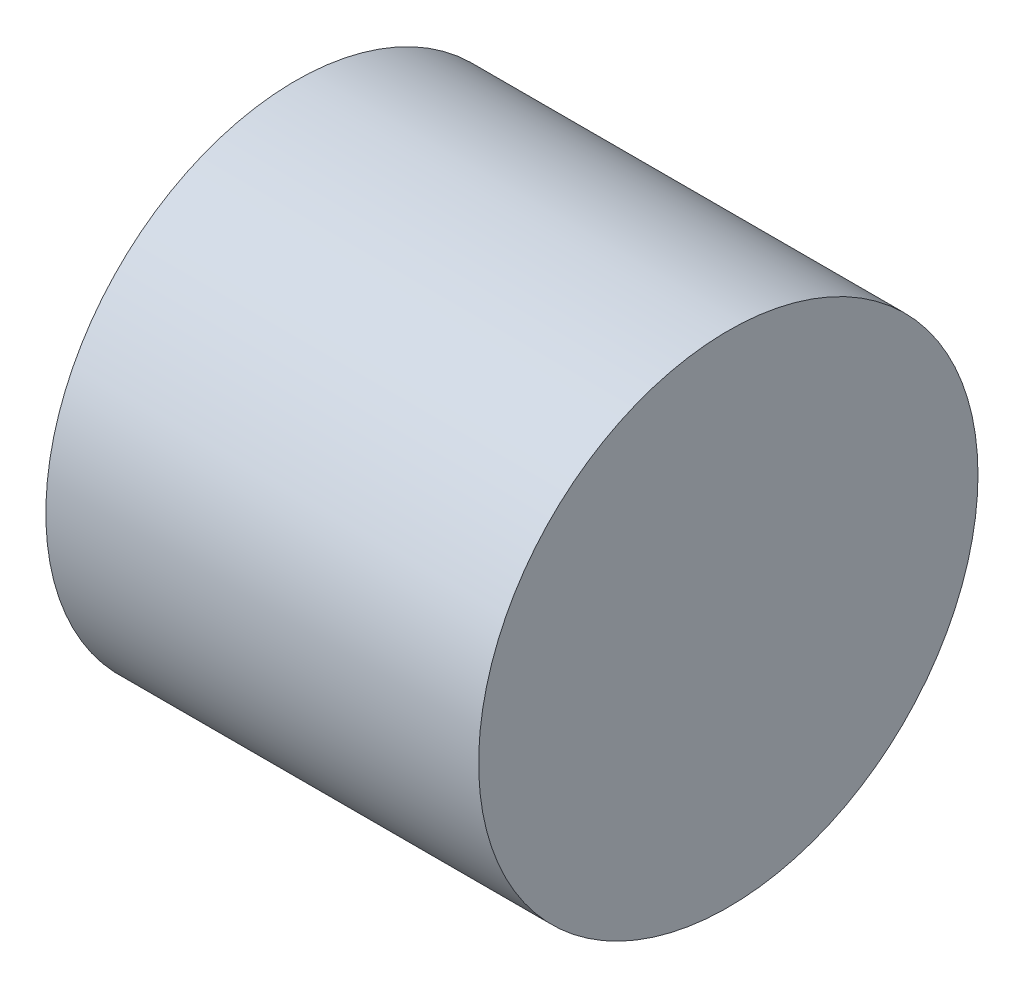
SolidWorks part; units mm, degrees
ref_plane "前视基准面" through (0, 0, 0) normal (0, 0, 1) x (1, 0, 0)
ref_plane "上视基准面" through (0, 0, 0) normal (0, 1, 0) x (1, 0, 0)
ref_plane "右视基准面" through (0, 0, 0) normal (1, 0, 0) x (0, 0, -1)
other "图形1"
other "图形 (闭合) -1"
sketch "草图1" plane through (0, 0, 0) normal (1, 0, 0) x (0, 0, -1)
  circle A0 centre (-21.3863, 21.0123) radius 5.7694
extrude "凸台-拉伸1" add sketch "草图1" along normal blind 10
sketch "草图2" plane through (0, 0, 0) normal (1, 0, 0) x (0, 0, -1)
  circle A0 centre (-21.218, 20.8436) radius 21.3693
  circle A1 centre (-21.218, 20.8436) radius 11.621
  dimension "D1" = 23.242
  dimension "D2" = 42.7386
